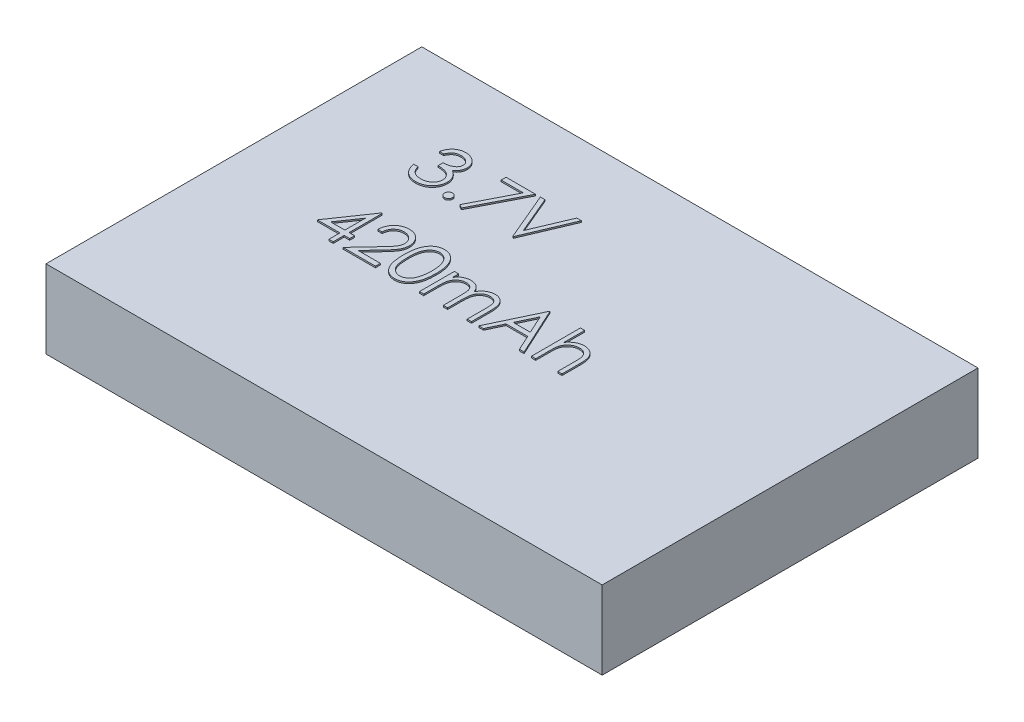
SolidWorks part; units mm, degrees
ref_plane "Front Plane" through (0, 0, 0) normal (0, 0, 1) x (1, 0, 0)
ref_plane "Top Plane" through (0, 0, 0) normal (0, 1, 0) x (1, 0, 0)
ref_plane "Right Plane" through (0, 0, 0) normal (1, 0, 0) x (0, 0, -1)
sketch "Sketch1" plane through (0, 0, 0) normal (0, 1, 0) x (1, 0, 0)
  line L1 (18.5, -12.5) -> (-18.5, -12.5)
  line L2 (18.5, -12.5) -> (18.5, 12.5)
  line L3 (18.5, 12.5) -> (-18.5, 12.5)
  line L4 (-18.5, -12.5) -> (-18.5, 12.5)
  line L5 (18.5, -12.5) -> (-18.5, 12.5) construction
  line L6 (18.5, 12.5) -> (-18.5, -12.5) construction
  point P0 (0, 0)
  dimension "D1" = 37
  dimension "D2" = 25
extrude "Boss-Extrude1" add sketch "Sketch1" along normal blind 5.2
sketch "Sketch2" plane through (0, 5.2, 0) normal (0, 1, 0) x (1, 0, 0)
  text T0 "3.7V\r\n420mAh"
extrude "Boss-Extrude2" add sketch "Sketch2" along normal blind 0.1
